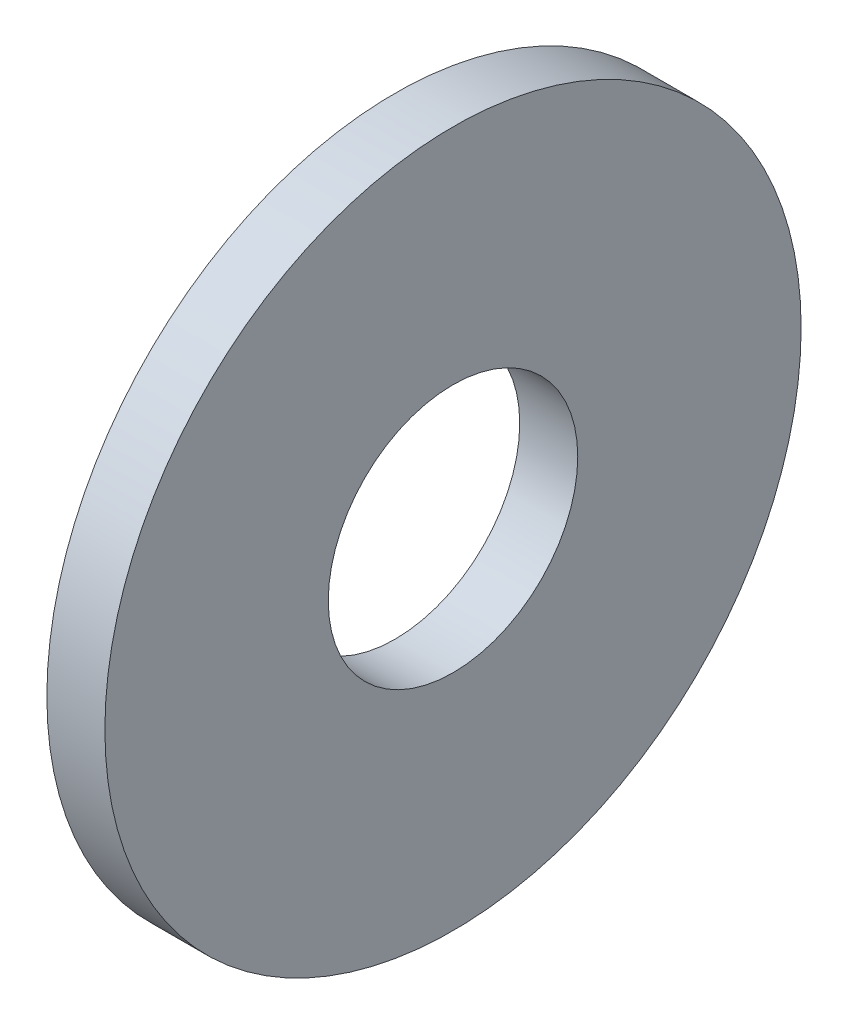
SolidWorks part; units mm, degrees
ref_plane "Plane1" through (0, 0, 0) normal (0, 0, 1) x (1, 0, 0)
ref_plane "Plane2" through (0, 0, 0) normal (0, 1, 0) x (1, 0, 0)
ref_plane "Plane3" through (0, 0, 0) normal (1, 0, 0) x (0, 0, -1)
sketch "Sketch1" plane through (0, 0, 0) normal (0, 0, 1) x (1, 0, 0)
  line L0 (-34.925, 0) -> (9.525, 0) construction
  line L1 (0, 2.15) -> (0, 6)
  line L2 (0, 6) -> (-1, 6)
  line L3 (-1, 6) -> (-1, 2.15)
  line L4 (-1, 2.15) -> (0, 2.15)
  dimension "Thickness" = 1
  dimension "Inside_dia" = 4.3
  dimension "Outside_dia" = 12
revolve "Base-Revolve" add sketch "Sketch1" angle 360 about L0
